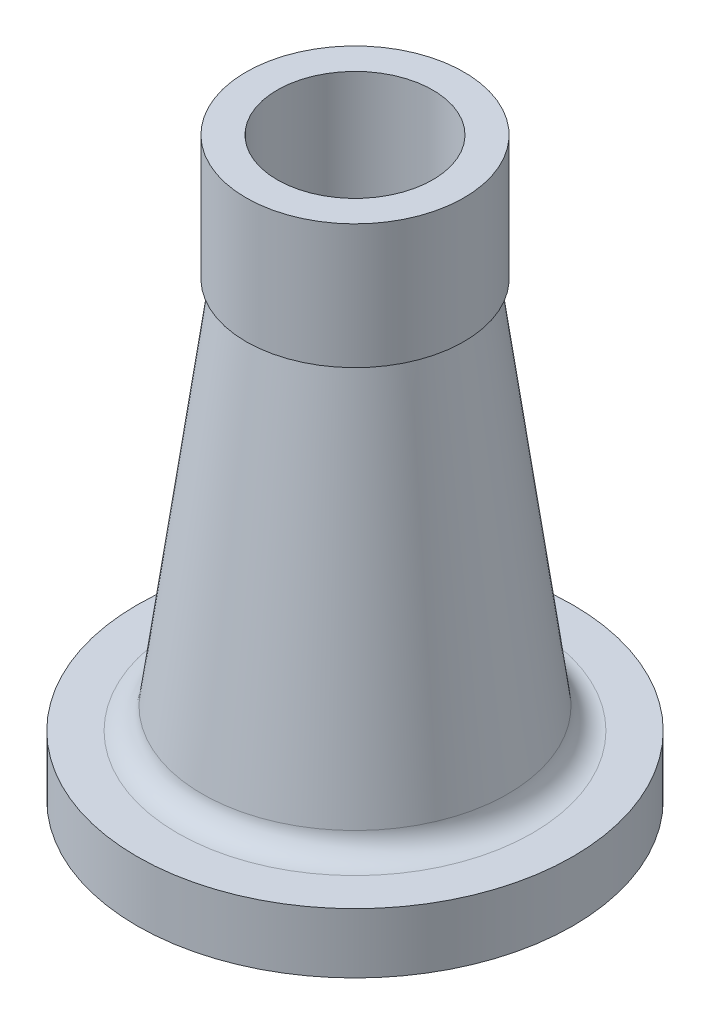
SolidWorks part; units mm, degrees
ref_plane "Front Plane" through (0, 0, 0) normal (0, 0, 1) x (1, 0, 0)
ref_plane "Top Plane" through (0, 0, 0) normal (0, 1, 0) x (1, 0, 0)
ref_plane "Right Plane" through (0, 0, 0) normal (1, 0, 0) x (0, 0, -1)
sketch "Sketch3" plane through (0, 0, 0) normal (0, 0, 1) x (1, 0, 0)
  line L0 (0, 0) -> (70, 0)
  line L1 (70, 0) -> (70, 19.2771)
  line L2 (70, 19.2771) -> (50, 19.2771)
  line L3 (50, 19.2771) -> (33, 145)
  line L4 (33, 145) -> (35, 145)
  line L5 (35, 145) -> (35, 185)
  line L6 (35, 185) -> (0, 185)
  line L7 (0, 280.6697) -> (0, 0) construction
  line L8 (24.9886, 185) -> (24.9886, 129.62)
  line L9 (24.9886, 129.62) -> (42.11, 2.9996)
  line L10 (50, 0) -> (50, 2.9996)
  line L11 (50, 2.9996) -> (0, 2.9996)
  dimension "D2" = 70
  dimension "D3" = 145
  dimension "D4" = 35
  dimension "D5" = 33
  dimension "D6" = 50
  dimension "D7" = 10
  dimension "D8" = 55.38
  dimension "D9" = 42.11
  dimension "D10" = 2.9996
  dimension "D11" = 50
  dimension "D12" = 40
revolve "Revolve1" add sketch "Sketch3" angle 360 about L7
fillet "Fillet1" radius 8 1 edges at (0, 19.2771, 50)
